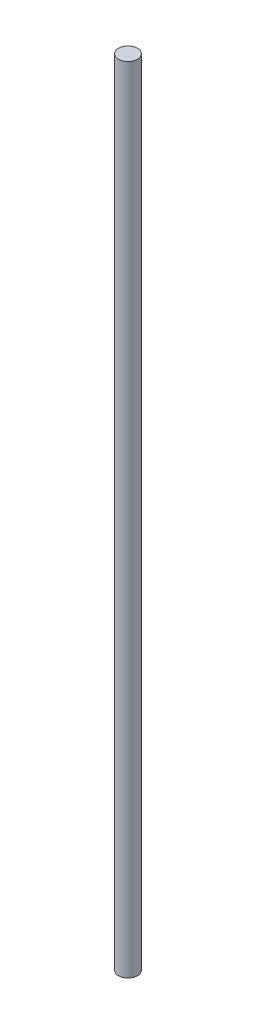
SolidWorks part; units mm, degrees
material "Custom Plastic"
ref_plane "Front Plane" through (0, 0, 0) normal (0, 0, 1) x (1, 0, 0)
ref_plane "Top Plane" through (0, 0, 0) normal (0, 1, 0) x (1, 0, 0)
ref_plane "Right Plane" through (0, 0, 0) normal (1, 0, 0) x (0, 0, -1)
sketch "Sketch1" plane through (0, 0, 0) normal (0, 1, 0) x (1, 0, 0)
  circle A0 centre (0, 0) radius 6
  dimension "D1" = 12
extrude "Boss-Extrude2" add sketch "Sketch1" along normal blind 500
